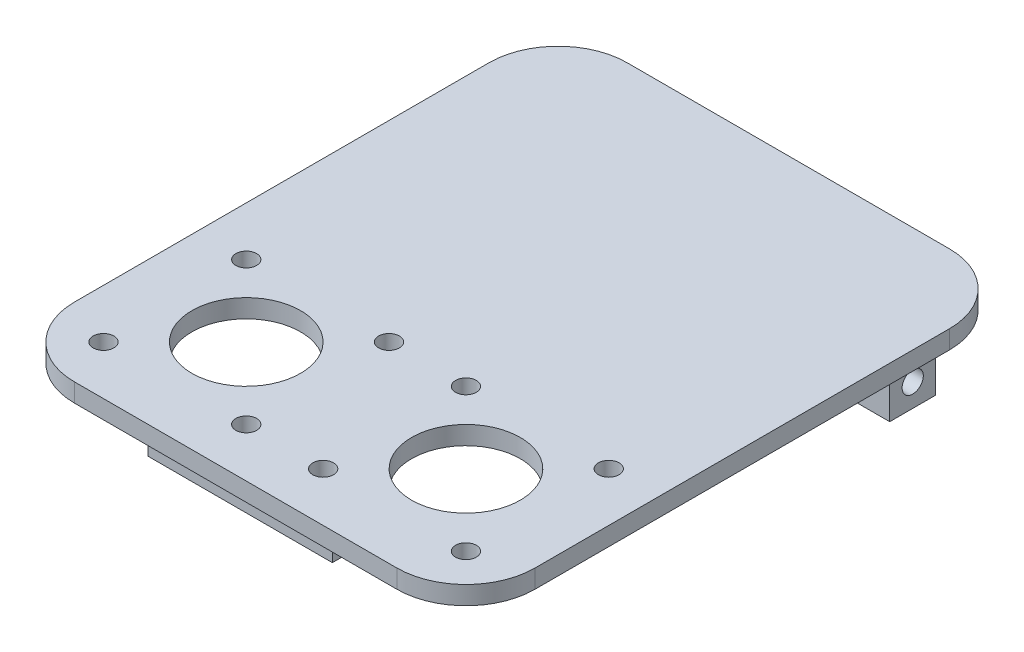
SolidWorks part; units mm, degrees
ref_plane "Front Plane" through (0, 0, 0) normal (0, 0, 1) x (1, 0, 0)
ref_plane "Top Plane" through (0, 0, 0) normal (0, 1, 0) x (1, 0, 0)
ref_plane "Right Plane" through (0, 0, 0) normal (1, 0, 0) x (0, 0, -1)
sketch "Sketch3" plane through (0, 0, 0) normal (0, 1, 0) x (1, 0, 0)
  line L1 (-50, 60) -> (50, 60)
  line L2 (-50, 60) -> (-50, -60)
  line L3 (-50, -60) -> (50, -60)
  line L4 (50, 60) -> (50, -60)
  line L5 (-50, 60) -> (50, -60) construction
  line L6 (-50, -60) -> (50, 60) construction
  point P0 (0, 0)
  dimension "D1" = 100
  dimension "D2" = 120
extrude "Boss-Extrude3" add sketch "Sketch3" along normal blind 4
sketch "Sketch5" plane through (0, 4, 0) normal (0, 1, 0) x (1, 0, 0)
  line L0 (-50, 60) -> (-50, -60) construction
  line L1 (50, -60) -> (50, 60) construction
  line L2 (-50, -60) -> (50, -60) construction
  line L4 (-39.35, -18.35) -> (-8.35, -18.35) construction
  line L5 (-39.35, -18.35) -> (-39.35, -49.35) construction
  line L6 (-39.35, -49.35) -> (-8.35, -49.35) construction
  line L7 (-8.35, -18.35) -> (-8.35, -49.35) construction
  line L8 (-39.35, -18.35) -> (-8.35, -49.35) construction
  line L9 (-39.35, -49.35) -> (-8.35, -18.35) construction
  line L10 (8.35, -18.35) -> (39.35, -18.35) construction
  line L11 (8.35, -18.35) -> (8.35, -49.35) construction
  line L12 (8.35, -49.35) -> (39.35, -49.35) construction
  line L13 (39.35, -18.35) -> (39.35, -49.35) construction
  line L14 (8.35, -18.35) -> (39.35, -49.35) construction
  line L15 (8.35, -49.35) -> (39.35, -18.35) construction
  circle A0 centre (-23.85, -33.85) radius 11.8
  circle A1 centre (23.85, -33.85) radius 11.8
  dimension "D1" = 23.6
  dimension "D2" = 23.6
  dimension "D3" = 26.15
  dimension "D4" = 26.15
  dimension "D5" = 26.15
  dimension "D6" = 26.15
  dimension "D7" = 31
  dimension "D8" = 31
  dimension "D9" = 31
  dimension "D10" = 31
hole_wizard "M4 Clearance Hole1" positions "Sketch13" profile "Sketch12" hole size "M4" standard "ANSI Metric" end condition through all
sketch "Sketch13" plane through (0, 4, 0) normal (0, 1, 0) x (1, 0, 0)
  point P0 (-8.35, -18.35)
  point P3 (-39.35, -18.35)
  point P6 (-39.35, -49.35)
  point P9 (-8.35, -49.35)
  point P12 (8.35, -18.35)
  point P15 (39.35, -18.35)
  point P18 (39.35, -49.35)
  point P21 (8.35, -49.35)
sketch "Sketch12" plane through (-8.35, 4, 18.35) normal (1, 0, 0) x (0, 0, 1)
  line L0 (0, 0) -> (0, 4)
  line L1 (0, 4) -> (2.25, 4)
  line L2 (2.25, 4) -> (2.25, 0)
  line L5 (2.25, 0) -> (0, 0)
  line L11 (0, -6.35) -> (0, 107.95) construction
  dimension "Thru Hole Dia." = 4.5
  dimension "Thru Hole Depth" = 4
extrude "Cut-Extrude3" cut sketch "Sketch5" against normal through all contours A1 | A0
fillet "Fillet1" radius 15 4 edges at (-50, 2, 60) (50, 2, 60) (50, 2, -60) (-50, 2, -60)
sketch "Sketch23" plane through (0, 0, 0) normal (0, -1, 0) x (1, 0, 0)
  line L0 (-50, -45) -> (-50, 45) construction
  line L1 (-47, -35) -> (-38, -35)
  line L2 (-47, -35) -> (-47, -45)
  line L3 (-47, -45) -> (-38, -45)
  line L4 (-38, -35) -> (-38, -45)
  line L5 (-47, -35) -> (-38, -45) construction
  line L6 (-47, -45) -> (-38, -35) construction
  line L7 (38, -35) -> (47, -35)
  line L8 (38, -35) -> (38, -45)
  line L9 (38, -45) -> (47, -45)
  line L10 (47, -35) -> (47, -45)
  line L11 (38, -35) -> (47, -45) construction
  line L12 (38, -45) -> (47, -35) construction
  line L13 (35, -60) -> (-35, -60) construction
  line L14 (50, 45) -> (50, -45) construction
  point P0 (-42.5, -40)
  point P5 (42.5, -40)
  dimension "D1" = 10
  dimension "D2" = 9
  dimension "D3" = 9
  dimension "D4" = 10
  dimension "D5" = 3
  dimension "D6" = 15
  dimension "D7" = 15
  dimension "D8" = 3
extrude "Boss-Extrude5" add sketch "Sketch23" along normal blind 10
sketch "Sketch26" plane through (0, 0, 0) normal (0, -1, 0) x (1, 0, 0)
  line L0 (-35, 60) -> (35, 60) construction
  line L1 (-20, 59) -> (20, 59)
  line L2 (-20, 59) -> (-20, 57)
  line L3 (-20, 57) -> (20, 57)
  line L4 (20, 59) -> (20, 57)
  line L5 (-20, 59) -> (20, 57) construction
  line L6 (-20, 57) -> (20, 59) construction
  line L7 (50, 45) -> (50, -45) construction
  point P0 (0, 58)
  dimension "D1" = 1
  dimension "D2" = 2
  dimension "D3" = 40
  dimension "D4" = 50
extrude "Boss-Extrude6" add sketch "Sketch26" along normal blind 3
sketch "Sketch27" plane through (-47, 0, 0) normal (-1, 0, 0) x (0, 0, 1)
  line L0 (-35, 0) -> (-45, 0) construction
  line L1 (-35, -10) -> (-35, 0) construction
  circle A0 centre (-40, -5) radius 2.3
  dimension "D1" = 4.6
  dimension "D2" = 5
  dimension "D3" = 5
extrude "Cut-Extrude4" cut sketch "Sketch27" against normal blind 6.6
sketch "Sketch28" plane through (47, 0, 0) normal (1, 0, 0) x (0, 0, -1)
  line L0 (45, -10) -> (45, 0) construction
  line L1 (45, 0) -> (35, 0) construction
  circle A0 centre (40, -5) radius 2.3
  dimension "D1" = 4.6
  dimension "D2" = 5
  dimension "D3" = 5
extrude "Cut-Extrude5" cut sketch "Sketch28" against normal blind 6.6
fillet "Fillet2" radius 2 1 edges at (38, 0, -40)
fillet "Fillet3" radius 2 1 edges at (-38, 0, -40)
fillet "Fillet4" radius 2 1 edges at (41.5, 0, -35)
fillet "Fillet5" radius 2 1 edges at (-41.5, 0, -35)
fillet "Fillet6" radius 2 1 edges at (41.5, 0, -45)
fillet "Fillet7" radius 2 1 edges at (-41.5, 0, -45)
